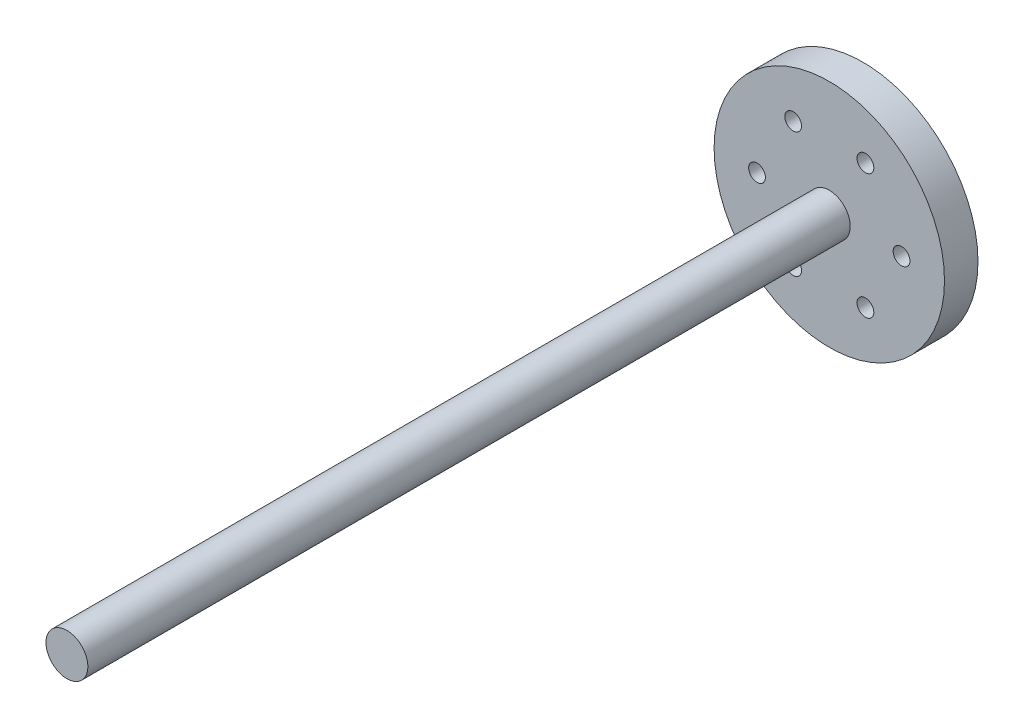
SolidWorks part; units mm, degrees
ref_plane "前视基准面" through (0, 0, 0) normal (0, 0, 1) x (1, 0, 0)
ref_plane "上视基准面" through (0, 0, 0) normal (0, 1, 0) x (1, 0, 0)
ref_plane "右视基准面" through (0, 0, 0) normal (1, 0, 0) x (0, 0, -1)
sketch "草图1" plane through (0, 0, 0) normal (0, 0, 1) x (1, 0, 0)
  circle A0 centre (0, 0) radius 27.5
  circle A1 centre (0, 0) radius 17.25 construction
  circle A2 centre (-17.25, 0) radius 2
  circle A3 centre (-8.625, 14.9389) radius 2
  circle A4 centre (8.625, 14.9389) radius 2
  circle A5 centre (17.25, 0) radius 2
  circle A6 centre (8.625, -14.9389) radius 2
  circle A7 centre (-8.625, -14.9389) radius 2
  point P18 (0, 0)
  dimension "D1" = 55
  dimension "D2" = 34.5
  dimension "D3" = 4
  dimension "D4" = 6
extrude "凸台-拉伸1" add sketch "草图1" along normal blind 8
sketch "草图2" plane through (0, 0, 8) normal (0, 0, 1) x (1, 0, 0)
  circle A0 centre (0, 0) radius 5
  circle A1 centre (0, 0) radius 27.5
  circle A2 centre (0, 0) radius 27.5 construction
  dimension "D2" = 10
  dimension "D1" = 0
extrude "凸台-拉伸2" add sketch "草图2" along normal blind 182
